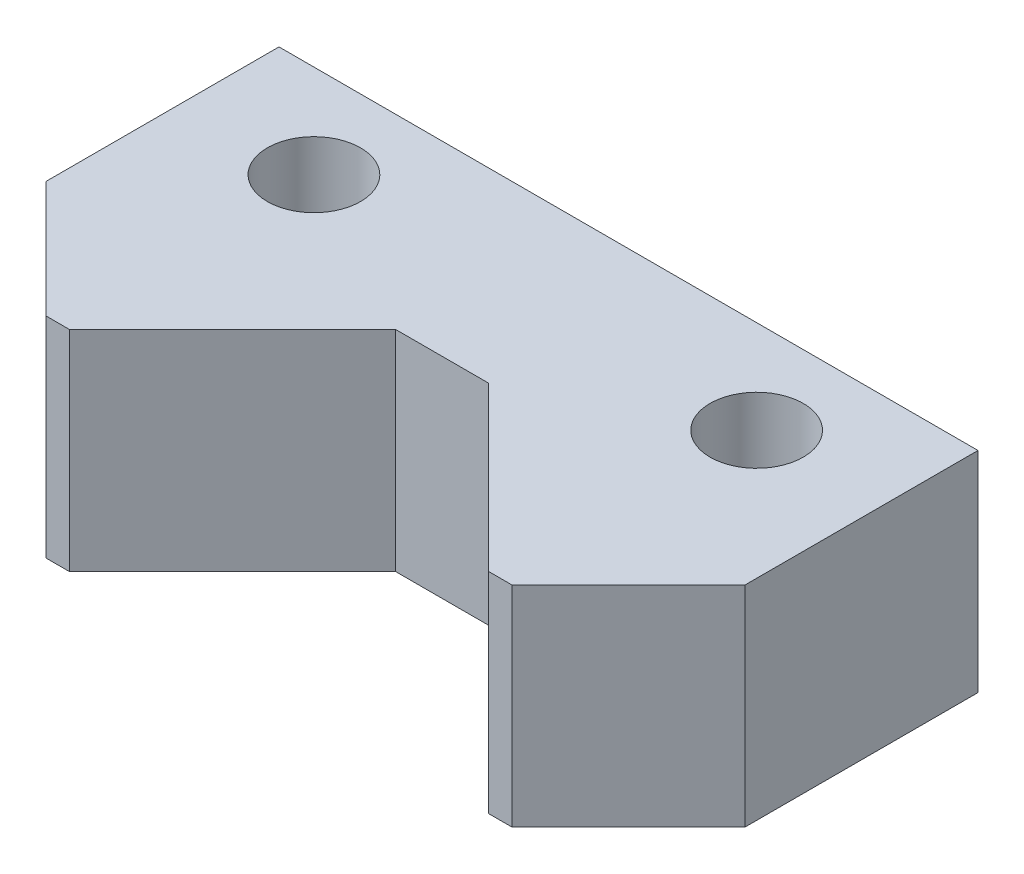
SolidWorks part; units mm, degrees
ref_plane "Piano frontale" through (0, 0, 0) normal (0, 0, 1) x (1, 0, 0)
ref_plane "Piano superiore" through (0, 0, 0) normal (0, 1, 0) x (1, 0, 0)
ref_plane "Piano destro" through (0, 0, 0) normal (1, 0, 0) x (0, 0, -1)
sketch "Schizzo1" plane through (0, 0, 0) normal (0, 1, 0) x (1, 0, 0)
  line L13 (0, 40.8718) -> (0, -30.0424) construction
  line L14 (30, 16) -> (-30, 16)
  line L15 (-30, 16) -> (-30, -4)
  line L16 (-30, -4) -> (-20, -14)
  line L17 (-20, -14) -> (-18, -14)
  line L18 (-18, -14) -> (-4, 0)
  line L19 (-4, 0) -> (4, 0)
  line L20 (20, -14) -> (18, -14)
  line L21 (18, -14) -> (4, 0)
  line L22 (30, -4) -> (20, -14)
  line L23 (30, 16) -> (30, -4)
  line L24 (-19, -14) -> (-19, 21.0663) construction
  point P2 (-30, -4.7826)
  point P11 (0, 0)
  point P15 (0, 16)
  dimension "D1" = 60
  dimension "D2" = 45
  dimension "D3" = 90
  dimension "D4" = 16
  dimension "D5" = 19
  dimension "D6" = 2
  dimension "D7" = 30
extrude "Estrusione-Estrusione1" add sketch "Schizzo1" along normal mid plane 18
hole_wizard "Foro Ø8.0 (8)-1" positions "Schizzo2" profile "Schizzo3" hole size "Ø8.0" standard "ISO" end condition up to next
sketch "Schizzo2" plane through (0, 9, 0) normal (0, 1, 0) x (1, 0, 0)
  line L0 (0, 16) -> (0, 0) construction
  line L1 (30, 16) -> (-30, 16) construction
  line L3 (-19, 20.3648) -> (-19, 3.2307) construction
  line L5 (-24.5051, 8) -> (-10.8624, 8) construction
  point P16 (-19, 8)
  point P19 (19, 8)
  dimension "D1" = 19
  dimension "D2" = 8
sketch "Schizzo3" plane through (19, 9, -8) normal (1, 0, 0) x (0, 0, 1)
  line L0 (0, 0) -> (0, 18)
  line L1 (0, 18) -> (4, 18)
  line L2 (4, 18) -> (4, 0)
  line L5 (4, 0) -> (0, 0)
  line L11 (0, -6.35) -> (0, 107.95) construction
  dimension "Thru Hole Dia." = 8
  dimension "Thru Hole Depth" = 18
